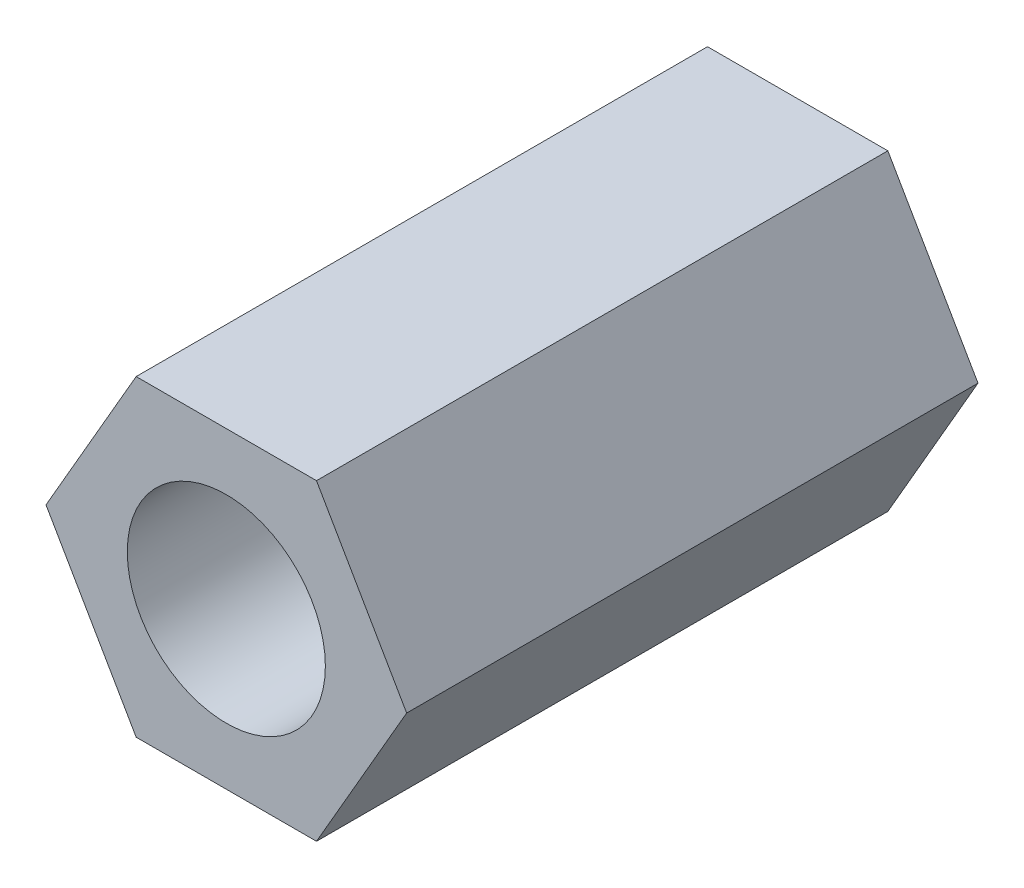
SolidWorks part; units mm, degrees
ref_plane "前视基准面" through (0, 0, 0) normal (0, 0, 1) x (1, 0, 0)
ref_plane "上视基准面" through (0, 0, 0) normal (0, 1, 0) x (1, 0, 0)
ref_plane "右视基准面" through (0, 0, 0) normal (1, 0, 0) x (0, 0, -1)
sketch "草图1" plane through (0, 0, 0) normal (0, 0, 1) x (1, 0, 0)
  line L1 (-23.6714, 0) -> (-11.8357, -20.5)
  line L2 (-11.8357, -20.5) -> (11.8357, -20.5)
  line L3 (11.8357, -20.5) -> (23.6714, 0)
  line L4 (23.6714, 0) -> (11.8357, 20.5)
  line L5 (11.8357, 20.5) -> (-11.8357, 20.5)
  line L6 (-11.8357, 20.5) -> (-23.6714, 0)
  circle A0 centre (0, 0) radius 20.5 construction
  dimension "D1" = 41
  dimension "D2" = 47.3427
extrude "凸台-拉伸1" add sketch "草图1" along normal blind 75
sketch "草图2" plane through (0, 0, 75) normal (0, 0, 1) x (1, 0, 0)
  circle A0 centre (0, 0) radius 13
  dimension "D1" = 26
extrude "切除-拉伸1" cut sketch "草图2" against normal blind 46
sketch "草图3" plane through (0, 0, 29) normal (0, 0, 1) x (1, 0, 0)
  circle A0 centre (0, 0) radius 11.1
  dimension "D1" = 22.2
extrude "切除-拉伸2" cut sketch "草图3" against normal blind 63
